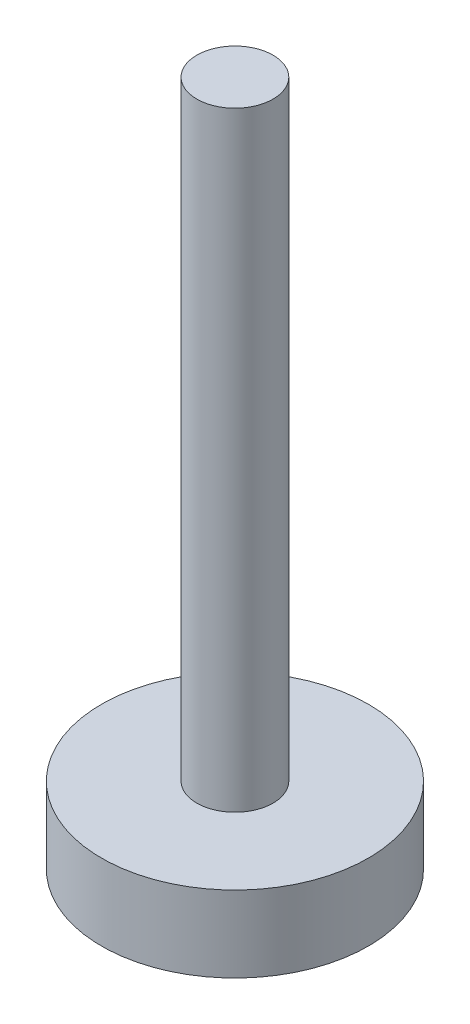
SolidWorks part; units mm, degrees
ref_plane "前视基准面" through (0, 0, 0) normal (0, 0, 1) x (1, 0, 0)
ref_plane "上视基准面" through (0, 0, 0) normal (0, 1, 0) x (1, 0, 0)
ref_plane "右视基准面" through (0, 0, 0) normal (1, 0, 0) x (0, 0, -1)
other "Configuration Table"
sketch "草图1" plane through (0, 0, 0) normal (0, 1, 0) x (1, 0, 0)
  circle A0 centre (0, 0) radius 5
  dimension "D1" = 10
extrude "凸台-拉伸1" add sketch "草图1" along normal blind 80
sketch "草图2" plane through (0, 0, 0) normal (0, -1, 0) x (1, 0, 0)
  circle A0 centre (0, 0) radius 17.5
  dimension "D1" = 35
extrude "凸台-拉伸2" add sketch "草图2" along normal blind 10
